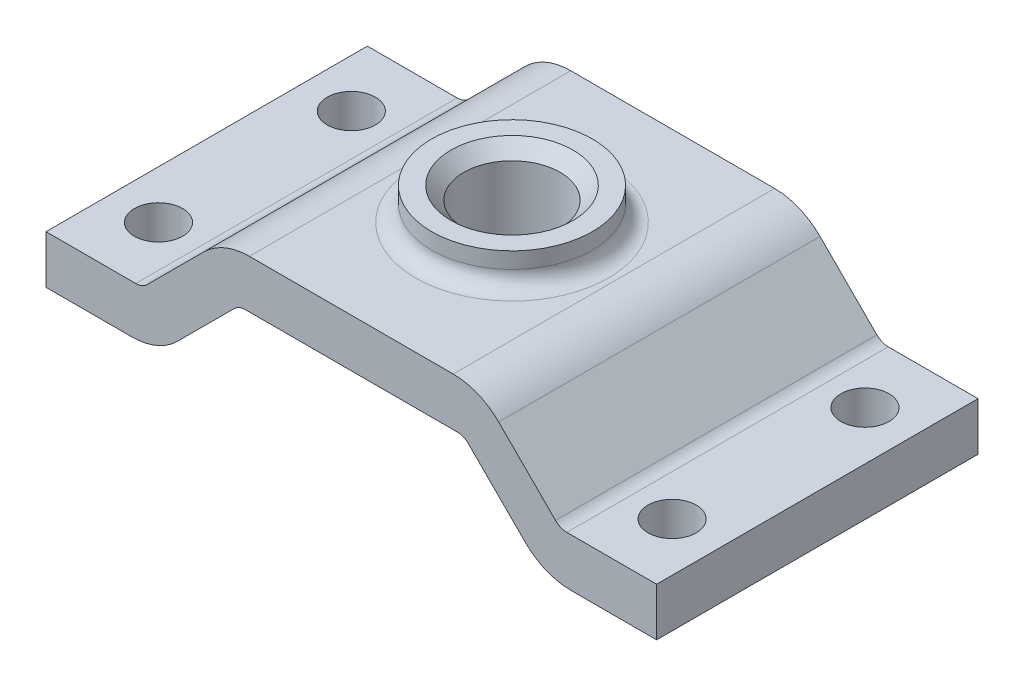
SolidWorks part; units mm, degrees
material "Chrome Stainless Steel"
ref_plane "Front Plane" through (0, 0, 0) normal (0, 0, 1) x (1, 0, 0)
ref_plane "Top Plane" through (0, 0, 0) normal (0, 1, 0) x (1, 0, 0)
ref_plane "Right Plane" through (0, 0, 0) normal (1, 0, 0) x (0, 0, -1)
sketch "Sketch1" plane through (0, 0, 0) normal (0, 0, 1) x (1, 0, 0)
  line L0 (-20.1395, 0) -> (20.1395, 0)
  line L1 (55, 0) -> (-55, 0) construction
  line L2 (29.1197, -3.7197) -> (40.3451, -14.9451)
  line L3 (42.5901, -15.875) -> (60.325, -15.875)
  line L4 (60.325, -15.875) -> (60.325, -25.4)
  line L5 (60.325, -25.4) -> (43.3605, -25.4)
  line L6 (34.3803, -21.6803) -> (23.1549, -10.4549)
  line L7 (20.9099, -9.525) -> (-20.9099, -9.525)
  line L8 (0, -55) -> (0, 55) construction
  line L9 (0, -9.525) -> (0, 0)
  line L10 (-34.3803, -21.6803) -> (-23.1549, -10.4549)
  line L11 (-60.325, -25.4) -> (-43.3605, -25.4)
  line L12 (-60.325, -15.875) -> (-60.325, -25.4)
  line L13 (-42.5901, -15.875) -> (-60.325, -15.875)
  line L14 (-29.1197, -3.7197) -> (-40.3451, -14.9451)
  arc A0 (40.3451, -14.9451) -> (42.5901, -15.875) centre (42.5901, -12.7) ccw
  arc A1 (20.9099, -9.525) -> (23.1549, -10.4549) centre (20.9099, -12.7) cw
  arc A2 (43.3605, -25.4) -> (34.3803, -21.6803) centre (43.3605, -12.7) cw
  arc A3 (29.1197, -3.7197) -> (20.1395, 0) centre (20.1395, -12.7) ccw
  arc A4 (-29.1197, -3.7197) -> (-20.1395, 0) centre (-20.1395, -12.7) cw
  arc A5 (-43.3605, -25.4) -> (-34.3803, -21.6803) centre (-43.3605, -12.7) ccw
  arc A6 (-20.9099, -9.525) -> (-23.1549, -10.4549) centre (-20.9099, -12.7) ccw
  arc A7 (-40.3451, -14.9451) -> (-42.5901, -15.875) centre (-42.5901, -12.7) cw
  point P15 (41.275, -15.875)
  point P18 (22.225, -9.525)
  point P23 (25.4, 0)
  point P38 (-25.4, 0)
  point P39 (-22.225, -9.525)
  point P40 (-41.275, -15.875)
  dimension "D8" = 3.175
  dimension "D9" = 12.7
  dimension "D1" = 25.4
  dimension "D2" = 15.875
  dimension "D3" = 15.875
  dimension "D4" = 9.525
  dimension "D5" = 22.225
  dimension "D6" = 9.525
  dimension "D7" = 19.05
extrude "Base" add sketch "Sketch1" along normal mid plane 63.5 contours L14 A7 L13 L12 L11 A5 L10 A6 L7 L9 L0 A4 | L2 A3 L0 L9 L7 A1 L6 A2 L5 L4 L3 A0
sketch "Sketch2" plane through (0, 0, 0) normal (0, 1, 0) x (1, 0, 0)
  circle A0 centre (0, 0) radius 15.875
  dimension "D1" = 31.75
extrude "Round Boss" add sketch "Sketch2" along normal blind 6.35 and the other way blind 25.4
sketch "Sketch3" plane through (0, 6.35, 0) normal (0, 1, 0) x (1, 0, 0)
  circle A0 centre (0, 0) radius 9.525
  dimension "D1" = 19.05
extrude "Center Hole" cut sketch "Sketch3" against normal through all
fillet "Fillet1" radius 3.175 2 edges at (0, -9.525, -15.875) (0, 0, 15.875)
chamfer "Chamfer1" distance 2.54 angle 45 1 edges at (0, 6.35, 9.525)
sketch "Sketch4" plane through (0, -15.875, 0) normal (0, 1, 0) x (1, 0, 0)
  line L0 (0, -17.4625) -> (0, 17.4625) construction
  line L1 (-17.4625, 0) -> (17.4625, 0) construction
  circle A0 centre (-50.8, 19.05) radius 4.7625
  circle A1 centre (-50.8, -19.05) radius 4.7625
  circle A2 centre (50.6904, -19.05) radius 4.7625
  circle A3 centre (50.6904, 19.05) radius 4.7625
  point P8 (0, 0)
  point P9 (0, 0)
  point P10 (0, 0)
  point P11 (0, 0)
  dimension "D1" = 9.525
  dimension "D2" = 50.8
  dimension "D3" = 19.05
  dimension "D4" = 50.6904
  dimension "D5" = 19.05
extrude "Rivet Holes" cut sketch "Sketch4" against normal through all
